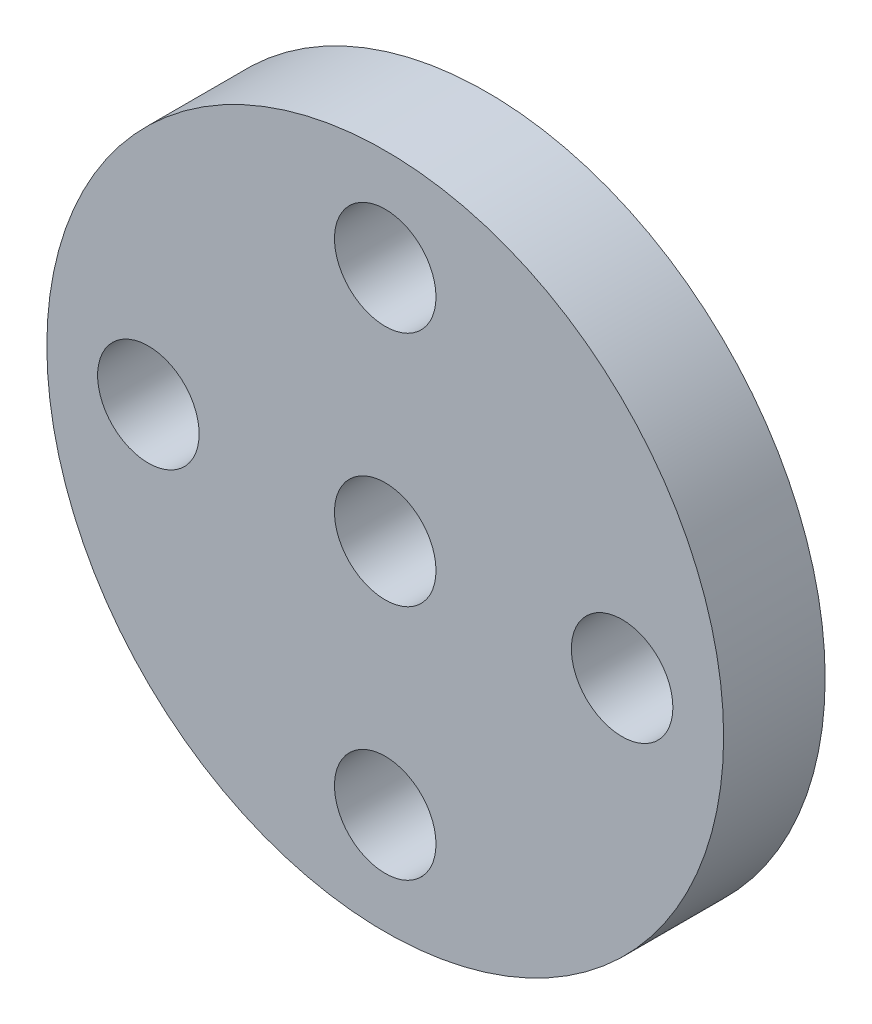
SolidWorks part; units mm, degrees
ref_plane "Спереди" through (0, 0, 0) normal (0, 0, 1) x (1, 0, 0)
ref_plane "Сверху" through (0, 0, 0) normal (0, 1, 0) x (1, 0, 0)
ref_plane "Справа" through (0, 0, 0) normal (1, 0, 0) x (0, 0, -1)
other "Configuration Table"
sketch "Эскиз1" plane through (0, 0, 0) normal (0, 0, 1) x (1, 0, 0)
  circle A0 centre (0, 0) radius 7 construction
  circle A1 centre (0, 7) radius 1.5
  circle A2 centre (7, 0) radius 1.5
  circle A3 centre (0, -7) radius 1.5
  circle A4 centre (-7, 0) radius 1.5
  circle A5 centre (0, 0) radius 1.5
  circle A6 centre (0, 0) radius 10
  dimension "D1" = 3
  dimension "D2" = 3
  dimension "D3" = 20
extrude "Бобышка-Вытянуть1" add sketch "Эскиз1" along normal blind 3
